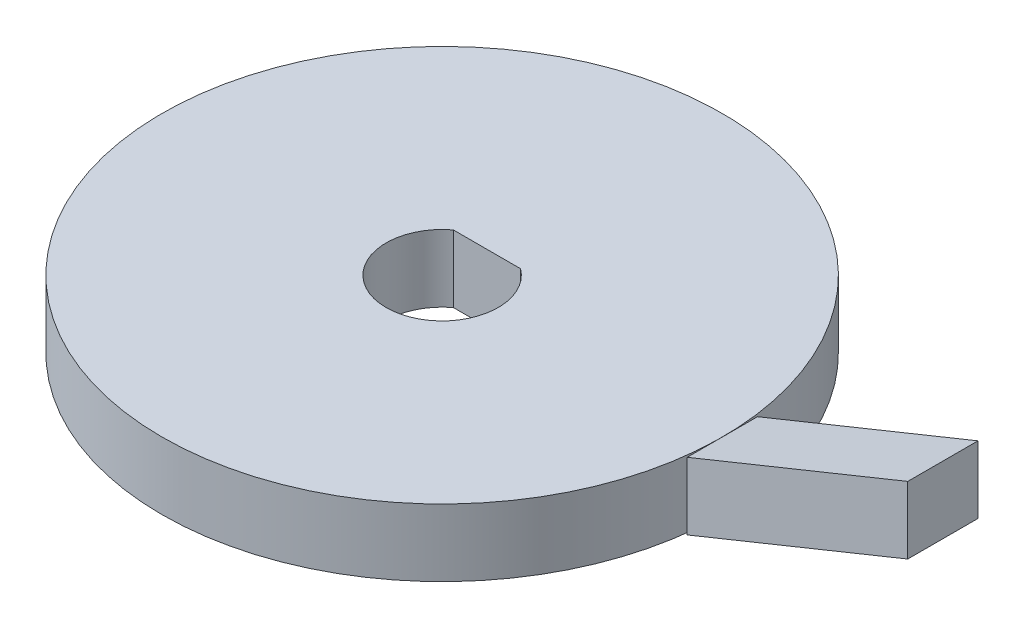
SolidWorks part; units mm, degrees
ref_plane "Front Plane" through (0, 0, 0) normal (0, 0, 1) x (1, 0, 0)
ref_plane "Top Plane" through (0, 0, 0) normal (0, 1, 0) x (1, 0, 0)
ref_plane "Right Plane" through (0, 0, 0) normal (1, 0, 0) x (0, 0, -1)
sketch "Sketch1" plane through (0, 0, 0) normal (0, 1, 0) x (1, 0, 0)
  line L0 (-1.5, 2) -> (1.5, 2)
  arc A0 (-1.5, 2) -> (1.5, 2) centre (0, 0) ccw
  circle A1 centre (0, 0) radius 12.5
  circle A2 centre (0, 0) radius 2.5 construction
  dimension "D2" = 5
  dimension "D3" = 3
  dimension "D1" = 10
extrude "Boss-Extrude1" add sketch "Sketch1" along normal mid plane 3
ref_point "Point1"
sketch "Sketch2" plane through (0, 0, 0) normal (0, 0, 1) x (1, 0, 0)
  line L0 (12.5, 0) -> (22.3362, 3.9865)
  line L1 (12.5, -1.5) -> (12.5, 1.5) construction
ref_plane "Plane1" through (12.5, 0, 0) normal (1, 0, 0) x (0, 0, -1)
sketch "Sketch3" plane through (12.5, 0, 0) normal (1, 0, 0) x (0, 0, -1)
  line L0 (12.5, 1.5) -> (-12.5, 1.5) construction
  line L1 (1.5673, -1.5) -> (-1.5673, -1.5)
  line L2 (1.5673, -1.5) -> (1.5673, 1.5)
  line L3 (1.5673, 1.5) -> (-1.5673, 1.5)
  line L4 (-1.5673, -1.5) -> (-1.5673, 1.5)
  line L5 (1.5673, -1.5) -> (-1.5673, 1.5) construction
  line L6 (1.5673, 1.5) -> (-1.5673, -1.5) construction
  point P0 (0, -0.061)
  point P1 (0, 0)
sweep "Sweep2" add profiles "Sketch3" path "Sketch2"
